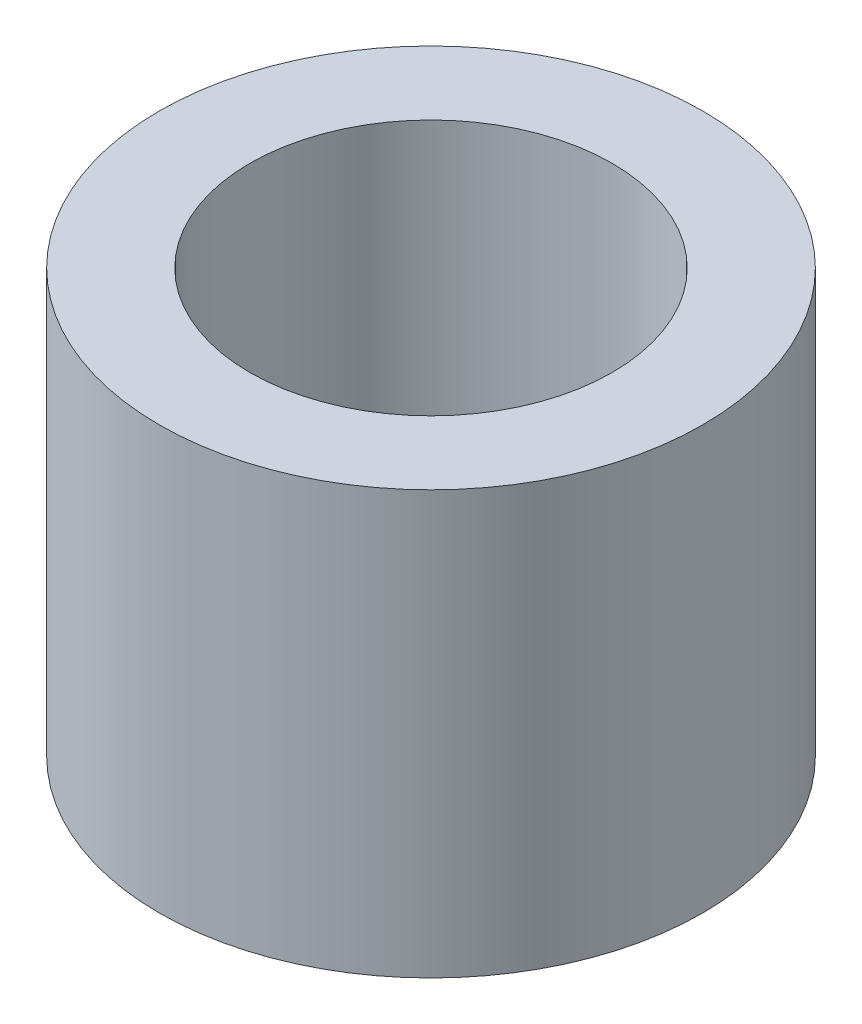
SolidWorks part; units mm, degrees
ref_plane "Front Plane" through (0, 0, 0) normal (0, 0, 1) x (1, 0, 0)
ref_plane "Top Plane" through (0, 0, 0) normal (0, 1, 0) x (1, 0, 0)
ref_plane "Right Plane" through (0, 0, 0) normal (1, 0, 0) x (0, 0, -1)
sketch "Sketch1" plane through (0, 0, 0) normal (1, 0, 0) x (0, 0, -1)
  line L0 (0, 15.5078) -> (0, -17.3664) construction
  line L1 (-18.6733, 0) -> (17.1631, 0) construction
  line L3 (-9, 7) -> (-6, 7)
  line L4 (-9, 7) -> (-9, -7)
  line L5 (-9, -7) -> (-6, -7)
  line L6 (-6, 7) -> (-6, -7)
  line L7 (-9, 7) -> (-6, -7) construction
  line L8 (-9, -7) -> (-6, 7) construction
  point P5 (-7.5, 0)
  point P10 (0, 0)
  dimension "D1" = 14
  dimension "D2" = 12
  dimension "D3" = 3
revolve "Revolve1" add sketch "Sketch1" angle 360 about L0
